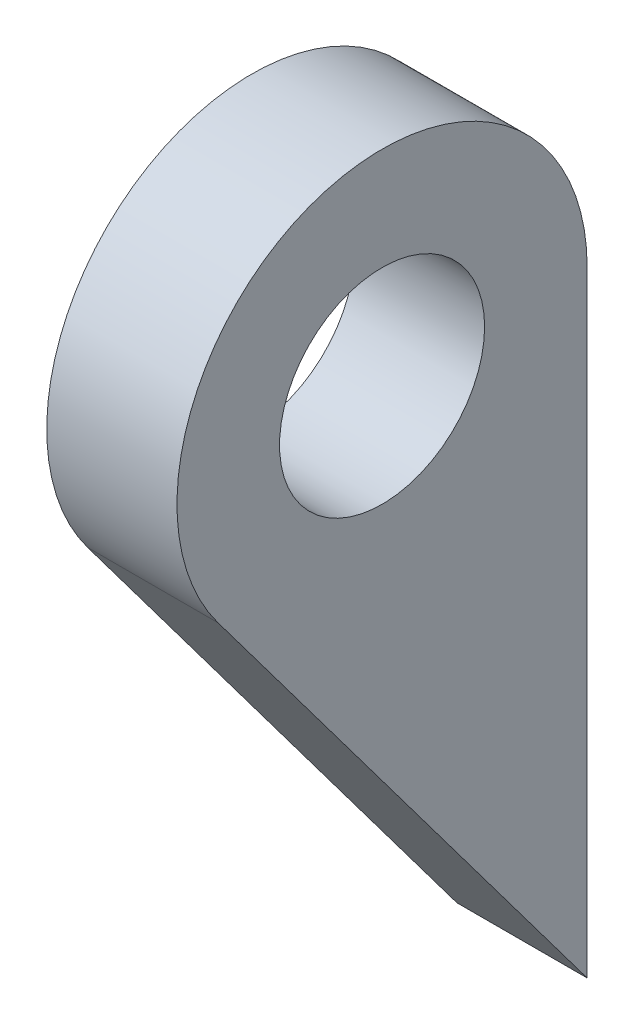
SolidWorks part; units mm, degrees
ref_plane "Front Plane" through (0, 0, 0) normal (0, 0, 1) x (1, 0, 0)
ref_plane "Top Plane" through (0, 0, 0) normal (0, 1, 0) x (1, 0, 0)
ref_plane "Right Plane" through (0, 0, 0) normal (1, 0, 0) x (0, 0, -1)
sketch "Sketch1" plane through (0, 0, 0) normal (0, 0, 1) x (1, 0, 0)
  line L1 (-193.65, 0) -> (193.65, 0)
  line L2 (-193.65, 0) -> (-193.65, -409.62)
  line L3 (-193.65, -409.62) -> (193.65, -409.62)
  line L4 (193.65, 0) -> (193.65, -409.62)
  point P5 (0, 0)
  dimension "D1" = 387.3
  dimension "D2" = 409.62
sketch "Sketch2" plane through (0, 0, 0) normal (1, 0, 0) x (0, 0, -1)
  line L0 (-0.0023, -10) -> (-0.0023, 10)
  line L2 (-0.0023, 10) -> (-5.0023, 10)
  line L3 (-9.0023, 2) -> (-0.0023, -10)
  circle A2 centre (-9.4571, 5.6462) radius 0.0001
  circle A4 centre (-5.0023, 5) radius 2.5
  circle A5 centre (-5.0023, 5) radius 5
  point P2 (0, 0)
  point P3 (0, 0)
  point P11 (0, 0)
  point P12 (0, 0)
  dimension "D3" = 5
  dimension "D4" = 5
  dimension "D1" = 5
  dimension "D2" = 10
extrude "Boss-Extrude3" add sketch "Sketch2" against normal mid plane 3.175 contours A5 L3 L0 | A5 A2 A4
